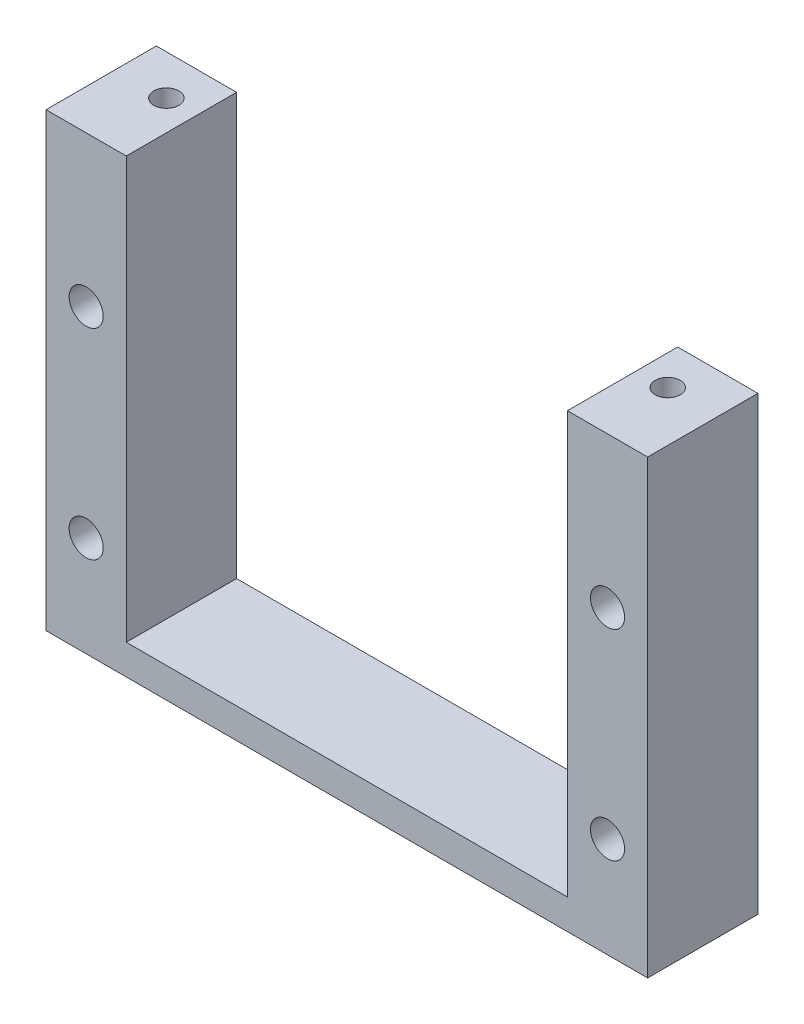
SolidWorks part; units mm, degrees
material "ABS PC"
ref_plane "Front Plane" through (0, 0, 0) normal (0, 0, 1) x (1, 0, 0)
ref_plane "Top Plane" through (0, 0, 0) normal (0, 1, 0) x (1, 0, 0)
ref_plane "Right Plane" through (0, 0, 0) normal (1, 0, 0) x (0, 0, -1)
sketch "Sketch1" plane through (0, 0, 0) normal (0, 0, 1) x (1, 0, 0)
  line L0 (0, 0) -> (60, 0)
  line L1 (0, 0) -> (0, 45)
  line L2 (60, 0) -> (60, 45)
  line L3 (0, 45) -> (60, 45)
  dimension "D1" = 60
  dimension "D2" = 45
extrude "Boss-Extrude1" add sketch "Sketch1" along normal blind 11
sketch "Sketch3" plane through (0, 45, 0) normal (0, 1, 0) x (1, 0, 0)
  line L0 (8, 0) -> (8, -11)
  line L1 (8, 0) -> (52, 0)
  line L2 (8, -11) -> (52, -11)
  line L3 (52, 0) -> (52, -11)
  line L6 (0, -11) -> (0, 0) construction
  line L8 (60, -11) -> (0, -11) construction
  line L9 (60, 0) -> (0, 0) construction
  dimension "D1" = 44
  dimension "D4" = 8
extrude "fan" cut sketch "Sketch3" against normal blind 42
sketch "Sketch4" plane through (0, 45, 0) normal (0, 1, 0) x (1, 0, 0)
  line L1 (0, -11) -> (0, 0) construction
  line L2 (60, -11) -> (52, -11) construction
  circle A0 centre (5, -4) radius 1.25
  circle A1 centre (55, -4) radius 1.25
  point P4 (0, -5.5)
  dimension "D1" = 2.5
  dimension "D2" = 50
  dimension "D3" = 5
  dimension "D4" = 7
extrude "screws" cut sketch "Sketch4" against normal blind 10
hole_wizard "Ø3.4 (3.4) Diameter Hole1" positions "Sketch7" profile "Sketch6" hole size "Ø3.4" standard "ANSI Metric" end condition through all
sketch "Sketch7" plane through (0, 0, 0) normal (0, 0, -1) x (-1, 0, 0)
  line L0 (-8, 45) -> (0, 45) construction
  line L1 (-8, 3) -> (-8, 45) construction
  line L2 (-52, 3) -> (-52, 45) construction
  point P0 (-4, 30)
  point P2 (-4, 10)
  point P4 (-56, 10)
  point P6 (-56, 30)
  dimension "D1" = 15
  dimension "D2" = 20
  dimension "D3" = 4
  dimension "D4" = 4
sketch "Sketch6" plane through (4, 30, 0) normal (1, 0, 0) x (0, 1, 0)
  line L0 (0, 0) -> (0, 11)
  line L1 (0, 11) -> (1.7, 11)
  line L2 (1.7, 11) -> (1.7, 0)
  line L5 (1.7, 0) -> (0, 0)
  line L11 (0, -6.35) -> (0, 107.95) construction
  dimension "Thru Hole Dia." = 3.4
  dimension "Thru Hole Depth" = 11
